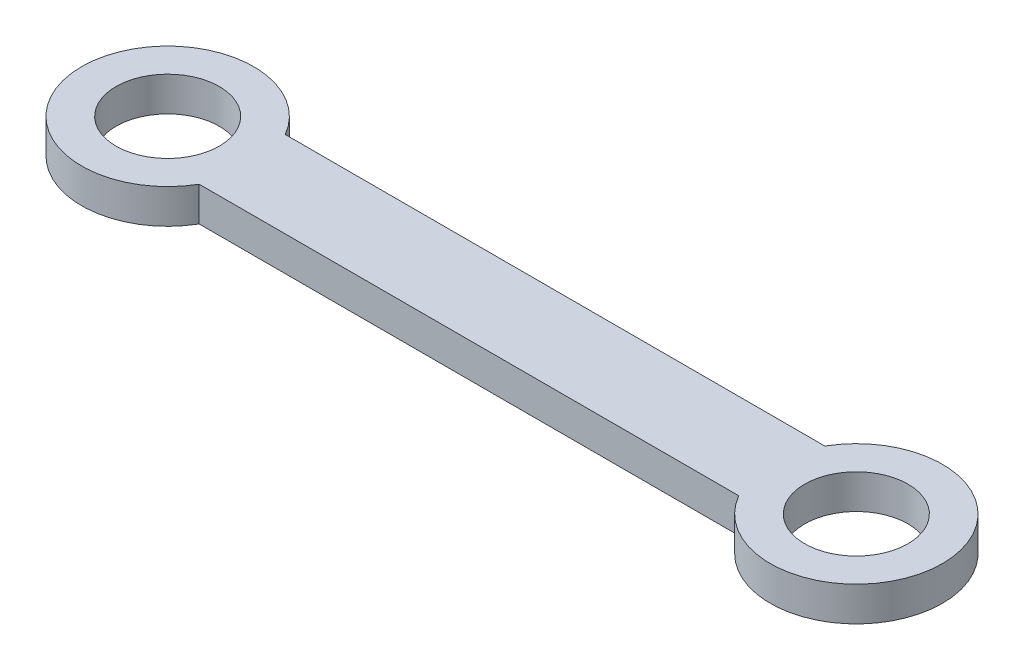
SolidWorks part; units mm, degrees
ref_plane "Front Plane" through (0, 0, 0) normal (0, 0, 1) x (1, 0, 0)
ref_plane "Top Plane" through (0, 0, 0) normal (0, 1, 0) x (1, 0, 0)
ref_plane "Right Plane" through (0, 0, 0) normal (1, 0, 0) x (0, 0, -1)
sketch "Sketch1" plane through (0, 0, 0) normal (0, 1, 0) x (1, 0, 0)
  line L0 (0, 4.9882) -> (0, -6.3821) construction
  line L1 (0, 0) -> (-20, 0) construction
  line L2 (15.6699, -2.5) -> (-15.6699, -2.5)
  line L3 (15.6699, 2.5) -> (-15.6699, 2.5)
  arc A2 (-15.6699, 2.5) -> (-15.6699, -2.5) centre (-20, 0) ccw
  circle A3 centre (-20, 0) radius 3
  circle A4 centre (20, 0) radius 3
  arc A5 (15.6699, 2.5) -> (15.6699, -2.5) centre (20, 0) cw
  point P5 (-7.5, 0)
  point P13 (0, 2.5)
  point P14 (0, -2.5)
  point P16 (7.5, 0)
  dimension "D1" = 6
  dimension "D2" = 2
  dimension "D4" = 5
  dimension "D3" = 20
extrude "Boss-Extrude1" add sketch "Sketch1" along normal blind 2
